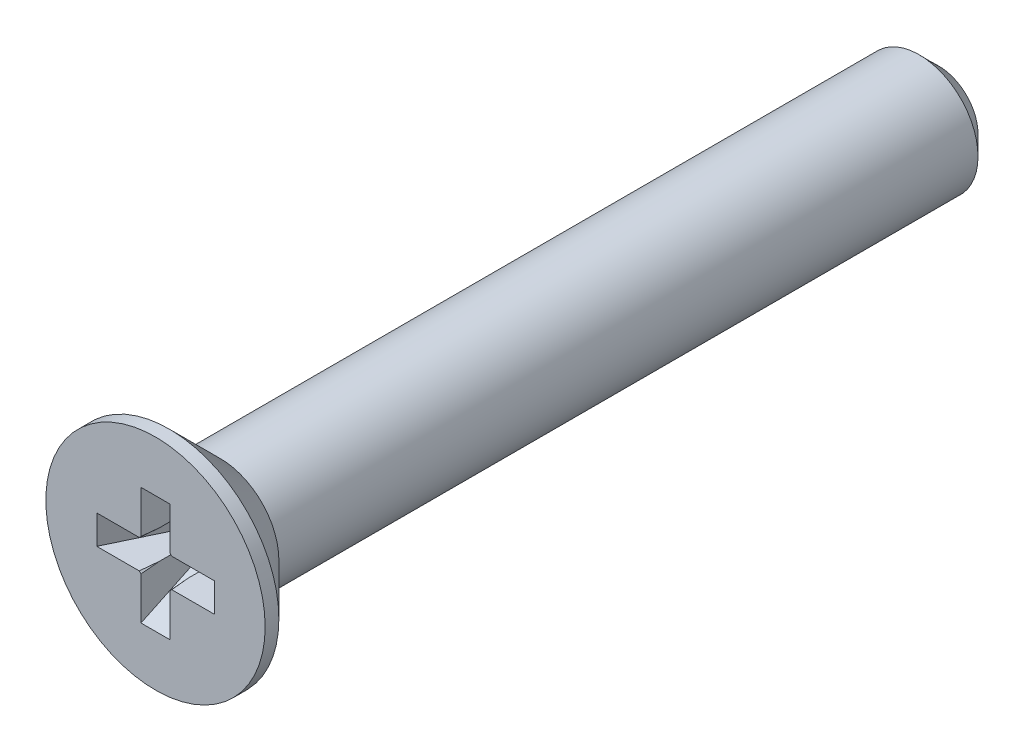
SolidWorks part; units mm, degrees
material "Легированная сталь"
ref_plane "Спереди" through (0, 0, 0) normal (0, 0, 1) x (1, 0, 0)
ref_plane "Сверху" through (0, 0, 0) normal (0, 1, 0) x (1, 0, 0)
ref_plane "Справа" through (0, 0, 0) normal (1, 0, 0) x (0, 0, -1)
sketch "Эскиз1" plane through (0, 0, 0) normal (0, 0, 1) x (1, 0, 0)
  line L12 (0, 2.8) -> (0.35, 2.8)
  line L13 (20, 0) -> (0, 0)
  line L14 (0, -2.8) -> (0.35, -2.8) construction
  line L15 (20, 1.5) -> (20, 0)
  line L16 (0.35, -2.8) -> (1.65, -1.5) construction
  line L17 (0, 0) -> (0, 2.8)
  line L18 (-6.35, 0) -> (82.55, 0) construction
  line L19 (16, 6.35) -> (16, -3.175) construction
  line L20 (1.65, 1.5) -> (20, 1.5)
  line L21 (1.65, -1.5) -> (20, -1.5) construction
  line L22 (0.35, 2.8) -> (1.65, 1.5)
  line L23 (2.15, 3.0875) -> (2.15, -6.4375) construction
  dimension "D9" = 3
  dimension "D10" = 20
  dimension "D11" = 1.65
  dimension "D12" = 5.6
  dimension "D13" = 90
  dimension "D14" = 0.35
  dimension "D15" = 0.5
  dimension "D16" = 4
revolve "Повернуть1" add sketch "Эскиз1" angle 360 about L18
cosmetic thread "Условное изображение резьбы1" parameters "D1"=12, "D2"=2.439
ref_plane "Плоскость1" through (2.1, 0, 0) normal (-1, 0, 0) x (0, 0, 1)
sketch "Эскиз2" plane through (0, 0, 0) normal (-1, 0, 0) x (0, 0, 1)
  line L1 (-0.37, 1.5) -> (0.37, 1.5)
  line L2 (-0.37, 1.5) -> (-0.37, -1.5)
  line L3 (-0.37, -1.5) -> (0.37, -1.5)
  line L4 (0.37, 1.5) -> (0.37, -1.5)
  line L5 (-0.37, 1.5) -> (0.37, -1.5) construction
  line L6 (-0.37, -1.5) -> (0.37, 1.5) construction
  point P0 (0, 0)
  dimension "D1" = 0.74
  dimension "D2" = 3
sketch "Эскиз3" plane through (2.1, 0, 0) normal (-1, 0, 0) x (0, 0, 1)
  line L1 (-0.37, 0.498) -> (0.37, 0.498)
  line L2 (-0.37, 0.498) -> (-0.37, -0.498)
  line L3 (-0.37, -0.498) -> (0.37, -0.498)
  line L4 (0.37, 0.498) -> (0.37, -0.498)
  line L5 (-0.37, 0.498) -> (0.37, -0.498) construction
  line L6 (-0.37, -0.498) -> (0.37, 0.498) construction
  point P0 (0, 0)
  dimension "D1" = 0.74
  dimension "D2" = 0.996
ref_axis "Ось1" through (20, 0, 0) along (-1, 0, 0)
loft "Вырез-По сечениям1" cut profiles "Эскиз2", "Эскиз3"
pattern_circular "Круговой массив1" count 2 over 90 about axis through (0, 0, 0) along (1, 0, 0) of "Вырез-По сечениям1"
ref_plane "Плоскость2" through (0, 0, 0) normal (0, 0, 1) x (1, 0, 0)
sketch "Эскиз4" plane through (0, 0, 0) normal (0, 0, 1) x (1, 0, 0)
  line L0 (0, 0) -> (0, 0.556)
  line L1 (0, 2.8) -> (0, -2.8) construction
  line L2 (0, 0.556) -> (2.1, 0.4092)
  line L3 (2.1, 0.4092) -> (2.2329, 0)
  line L4 (20, 0) -> (1.65, 0) construction
  line L5 (2.2329, 0) -> (0, 0)
  line L6 (-0.8992, 0) -> (-35.5405, 0) construction
  line L7 (2.1, 2.585) -> (2.1, -2.585) construction
  dimension "D1" = 4
  dimension "D2" = 18
  dimension "D3" = 1.112
revolve "Вырез-Повернуть1" cut sketch "Эскиз4" angle 360 about L6
chamfer "Фаска1" distance 0.5 angle 45 1 edges at (20, 0, 1.5)
other "PropertyManager"
move or copy body "Тело-Переместить/Копировать1" bodies to move or copy 104 copy no rotation origin (0, 0, 0) rotation axis (0, 1, 0) rotation angle 90
